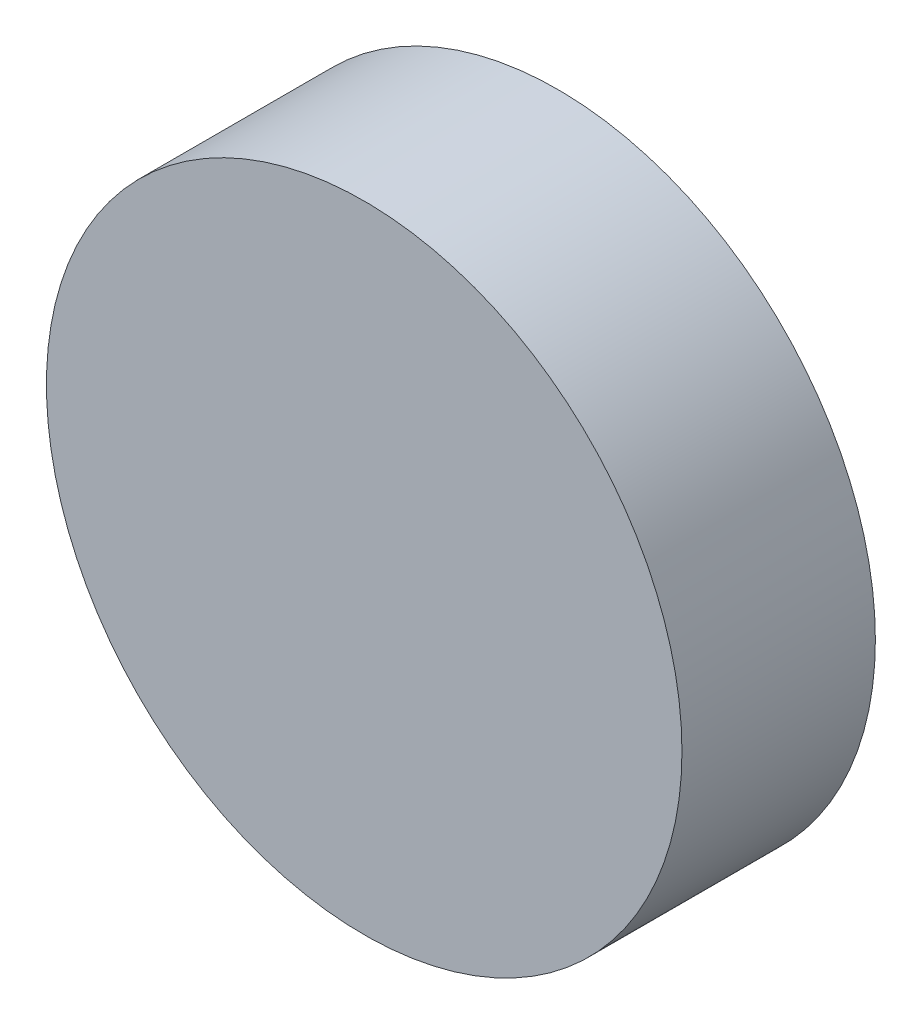
SolidWorks part; units mm, degrees
ref_plane "Front Plane" through (0, 0, 0) normal (0, 0, 1) x (1, 0, 0)
ref_plane "Top Plane" through (0, 0, 0) normal (0, 1, 0) x (1, 0, 0)
ref_plane "Right Plane" through (0, 0, 0) normal (1, 0, 0) x (0, 0, -1)
sketch "Sketch1" plane through (0, 0, 0) normal (0, 0, 1) x (1, 0, 0)
  circle A0 centre (0, 0) radius 46
  dimension "D1" = 92
extrude "Boss-Extrude1" add sketch "Sketch1" along normal blind 28
sketch "Sketch4" plane through (0, 0, 0) normal (0, 0, -1) x (-1, 0, 0)
  line L0 (0, 0) -> (0, 46) construction
  line L1 (0, 0) -> (-32.5269, 32.5269) construction
  circle A0 centre (0, 0) radius 46 construction
  circle A1 centre (-14.1421, 14.1421) radius 1.5
  circle A2 centre (14.1421, 14.1421) radius 1.5
  circle A3 centre (-14.1421, -14.1421) radius 1.5
  circle A4 centre (14.1421, -14.1421) radius 1.5
  dimension "D2" = 3
  dimension "D3" = 20
  dimension "D1" = 45
  dimension "D4" = 20
extrude "Cut-Extrude1" cut sketch "Sketch4" against normal blind 5
sketch "Sketch2" plane through (0, 0, 0) normal (0, 0, -1) x (-1, 0, 0)
  circle A0 centre (0, 0) radius 10
  dimension "D1" = 20
extrude "Boss-Extrude2" add sketch "Sketch2" along normal blind 2
